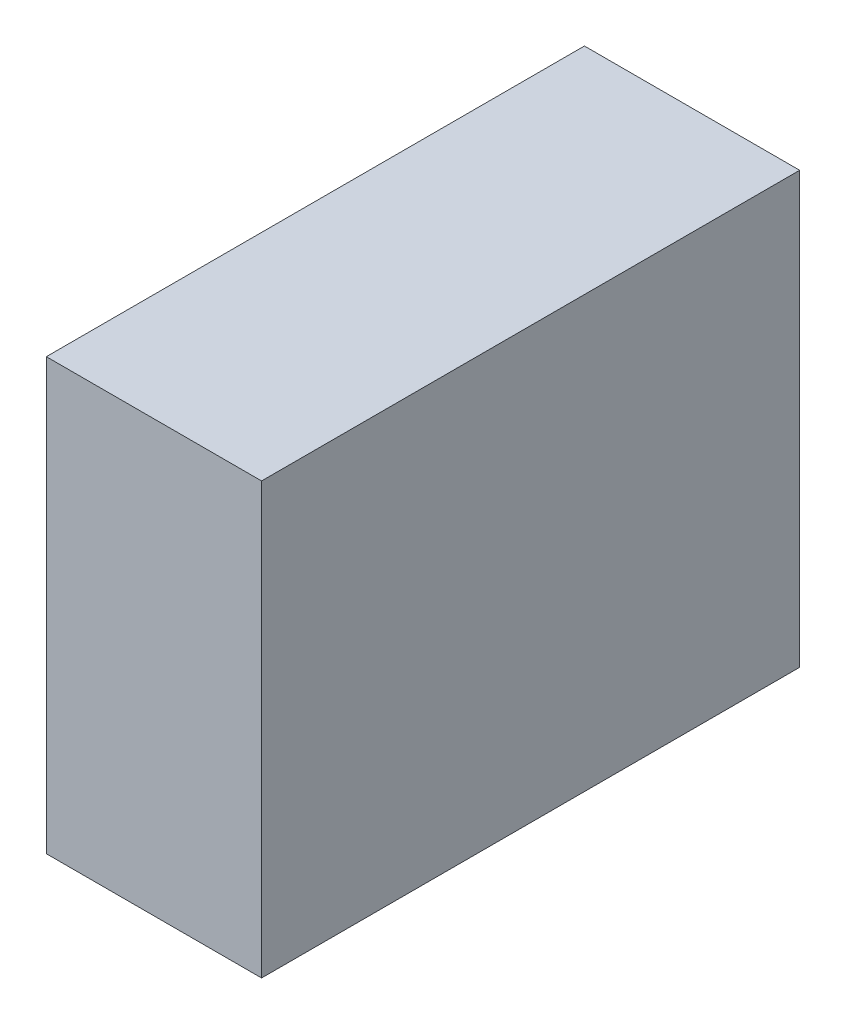
SolidWorks part; units mm, degrees
ref_plane "Front Plane" through (0, 0, 0) normal (0, 0, 1) x (1, 0, 0)
ref_plane "Top Plane" through (0, 0, 0) normal (0, 1, 0) x (1, 0, 0)
ref_plane "Right Plane" through (0, 0, 0) normal (1, 0, 0) x (0, 0, -1)
sketch "Sketch1" plane through (0, 0, 0) normal (0, 0, 1) x (1, 0, 0)
  line L1 (101.6, -203.2) -> (-101.6, -203.2)
  line L2 (101.6, -203.2) -> (101.6, 203.2)
  line L3 (101.6, 203.2) -> (-101.6, 203.2)
  line L4 (-101.6, -203.2) -> (-101.6, 203.2)
  line L5 (101.6, -203.2) -> (-101.6, 203.2) construction
  line L6 (101.6, 203.2) -> (-101.6, -203.2) construction
  point P0 (0, 0)
  dimension "D1" = 406.4
  dimension "D2" = 203.2
extrude "Boss-Extrude1" add sketch "Sketch1" along normal mid plane 508
